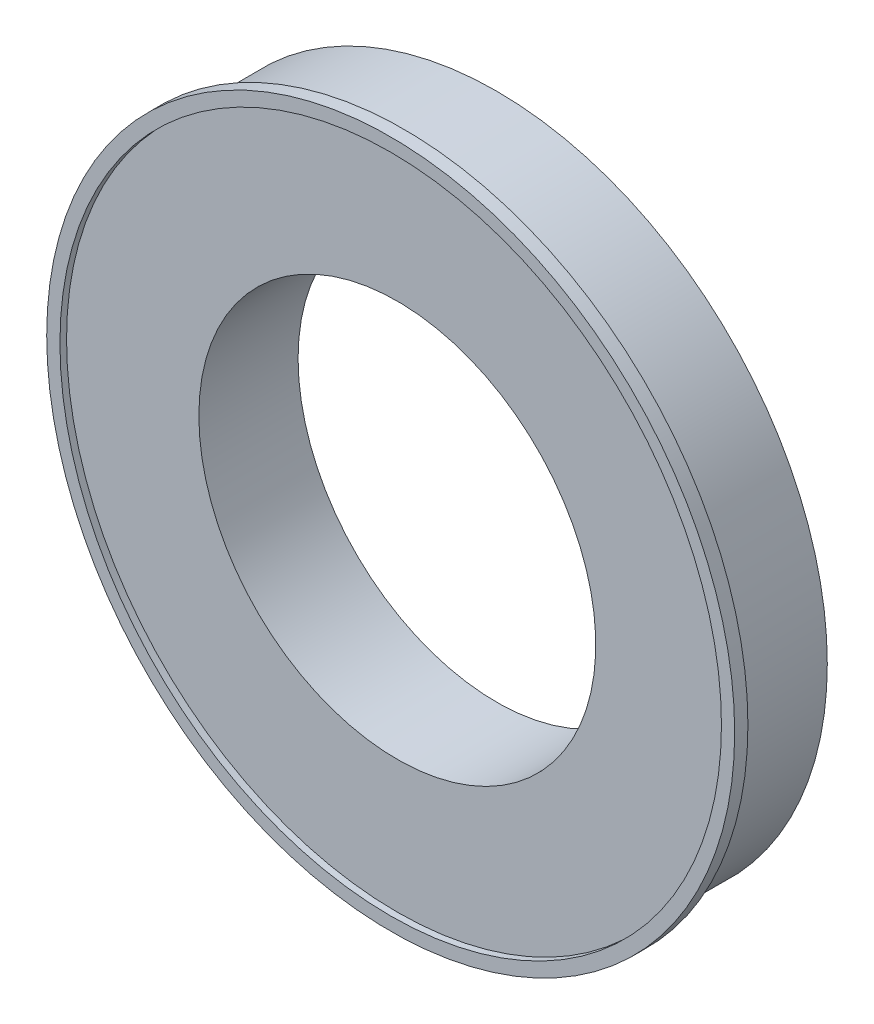
SolidWorks part; units mm, degrees
ref_plane "Front Plane" through (0, 0, 0) normal (0, 0, 1) x (1, 0, 0)
ref_plane "Top Plane" through (0, 0, 0) normal (0, 1, 0) x (1, 0, 0)
ref_plane "Right Plane" through (0, 0, 0) normal (1, 0, 0) x (0, 0, -1)
sketch "Sketch1" plane through (0, 0, 0) normal (0, 0, 1) x (1, 0, 0)
  circle A0 centre (0, 0) radius 38.1
  circle A1 centre (0, 0) radius 63.5
  dimension "D1" = 76.2
  dimension "D2" = 127
extrude "Boss-Extrude1" add sketch "Sketch1" along normal mid plane 19.05
sketch "Sketch2" plane through (0, 0, 9.525) normal (0, 0, 1) x (1, 0, 0)
  circle A1 centre (0, 0) radius 63.5 construction
  circle A2 centre (0, 0) radius 66.04
  circle A3 centre (0, 0) radius 66.04
  circle A4 centre (0, 0) radius 63.5
  dimension "D1" = 2.54
extrude "Boss-Extrude2" add sketch "Sketch2" along normal mid plane 2.54
